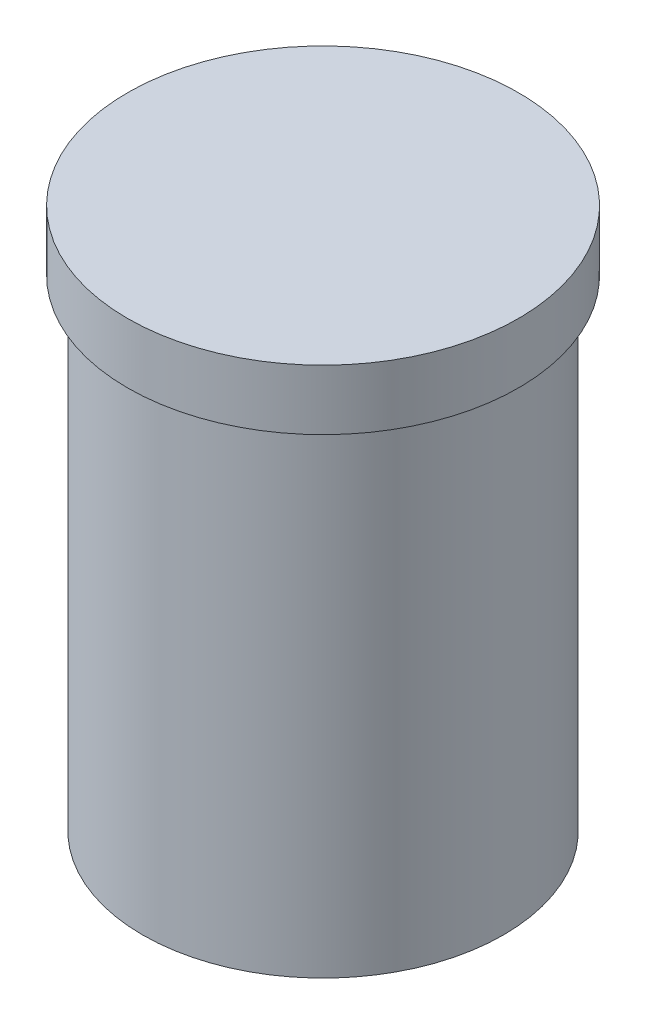
SolidWorks part; units mm, degrees
material "Oak"
ref_plane "Front" through (0, 0, 0) normal (0, 0, 1) x (1, 0, 0)
ref_plane "Top" through (0, 0, 0) normal (0, 1, 0) x (1, 0, 0)
ref_plane "Right" through (0, 0, 0) normal (1, 0, 0) x (0, 0, -1)
sketch "Sketch1" plane through (0, 0, 0) normal (0, 1, 0) x (1, 0, 0)
  circle A0 centre (0, 0) radius 38.1
  dimension "D1" = 76.2
extrude "Boss-Extrude1" add sketch "Sketch1" along normal blind 101.6
sketch "Sketch2" plane through (0, 101.6, 0) normal (0, 1, 0) x (1, 0, 0)
  circle A0 centre (0, 0) radius 41.275
  dimension "D1" = 82.55
extrude "Boss-Extrude2" add sketch "Sketch2" along normal blind 12.7
